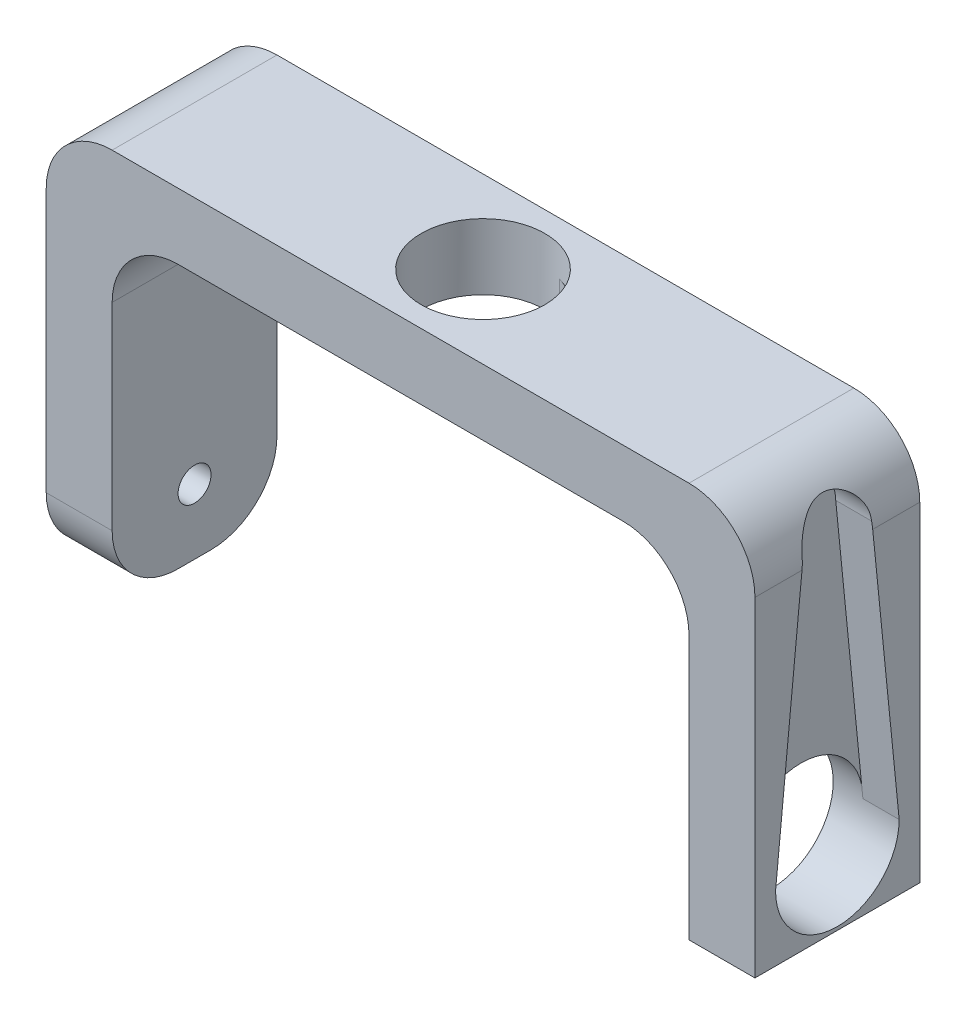
SolidWorks part; units mm, degrees
ref_plane "Front Plane" through (0, 0, 0) normal (0, 0, 1) x (1, 0, 0)
ref_plane "Top Plane" through (0, 0, 0) normal (0, 1, 0) x (1, 0, 0)
ref_plane "Right Plane" through (0, 0, 0) normal (1, 0, 0) x (0, 0, -1)
sketch "Sketch1" plane through (0, 0, 0) normal (0, 0, 1) x (1, 0, 0)
  line L0 (-17.5, 0) -> (17.5, 0)
  line L1 (17.5, 0) -> (17.5, -20)
  line L2 (-17.5, 0) -> (-17.5, -20)
  point P3 (0, 0)
  dimension "D1" = 35
  dimension "D2" = 20
  dimension "D3" = 20
extrude "Extrude-Thin1" add sketch "Sketch1" along normal blind 10 thin thin type one direction wall 4
fillet "Fillet1" radius 4 4 edges at (21.5, 4, 5) (-21.5, 4, 5) (17.5, 0, 5) (-17.5, 0, 5)
sketch "Sketch3" plane through (17.5, 0, 0) normal (-1, 0, 0) x (0, 0, 1)
  line L16 (1.25, -16.05) -> (2.9, 0.45)
  line L17 (7.1, 0.45) -> (8.75, -16.05)
  line L18 (10, -20) -> (0, -20) construction
  arc A3 (1.3243, -15.3074) -> (8.6757, -15.3074) centre (5, -16.05) ccw
  arc A4 (7.1, 0.45) -> (2.9, 0.45) centre (5, 0.45) ccw
  point P10 (5, -20)
  point P11 (5, -19.8)
  line M14 (10, -4) -> (0, -4)
  dimension "D2" = 7.5
  dimension "D1" = 4.2
  dimension "D3" = 0.2
  dimension "D4" = 16.5
extrude "Cut-Extrude1" cut sketch "Sketch3" against normal through all from offset 1.8 contours L16 A3 L17 M14 | L17 A4 L16 M14 offset against normal yes
sketch "Sketch10" plane through (19.3, 0, 0) normal (1, 0, 0) x (0, 0, -1)
  circle A0 centre (-5, -16.05) radius 3.75
  dimension "D1" = 7.5
extrude "Cut-Extrude7" cut sketch "Sketch10" against normal blind 10
sketch "Sketch4" plane through (-21.5, 0, 0) normal (-1, 0, 0) x (0, 0, 1)
  circle A1 centre (5, -16.05) radius 1
  dimension "D1" = 2
extrude "Cut-Extrude2" cut sketch "Sketch4" against normal blind 6
fillet "Fillet2" radius 4 2 edges at (-19.5, -20, 0) (-19.5, -20, 10)
sketch "Sketch8" plane through (0, 4, 0) normal (0, 1, 0) x (1, 0, 0)
  line L0 (17.5, -10) -> (17.5, 0) construction
  line L1 (1.0342, -8.6046) -> (16, -6.5)
  line L6 (16, -3.5) -> (1.0342, -1.3954)
  arc A0 (1.0342, -1.3954) -> (1.0342, -8.6046) centre (0, -5) ccw
  arc A1 (16, -6.5) -> (16, -3.5) centre (16, -5) ccw
  point P4 (17.5, -5)
  dimension "D1" = 7.5
  dimension "D2" = 3
  dimension "D3" = 16
  dimension "D4" = 16.4658
  dimension "D5" = 16.4658
extrude "Cut-Extrude5" cut sketch "Sketch8" against normal through all from offset 1.8 offset against normal yes
sketch "Sketch12" plane through (0, 2.2, 0) normal (0, -1, 0) x (1, 0, 0)
  circle A0 centre (0, 5) radius 3.75
  dimension "D1" = 7.5
extrude "Cut-Extrude9" cut sketch "Sketch12" against normal blind 10
